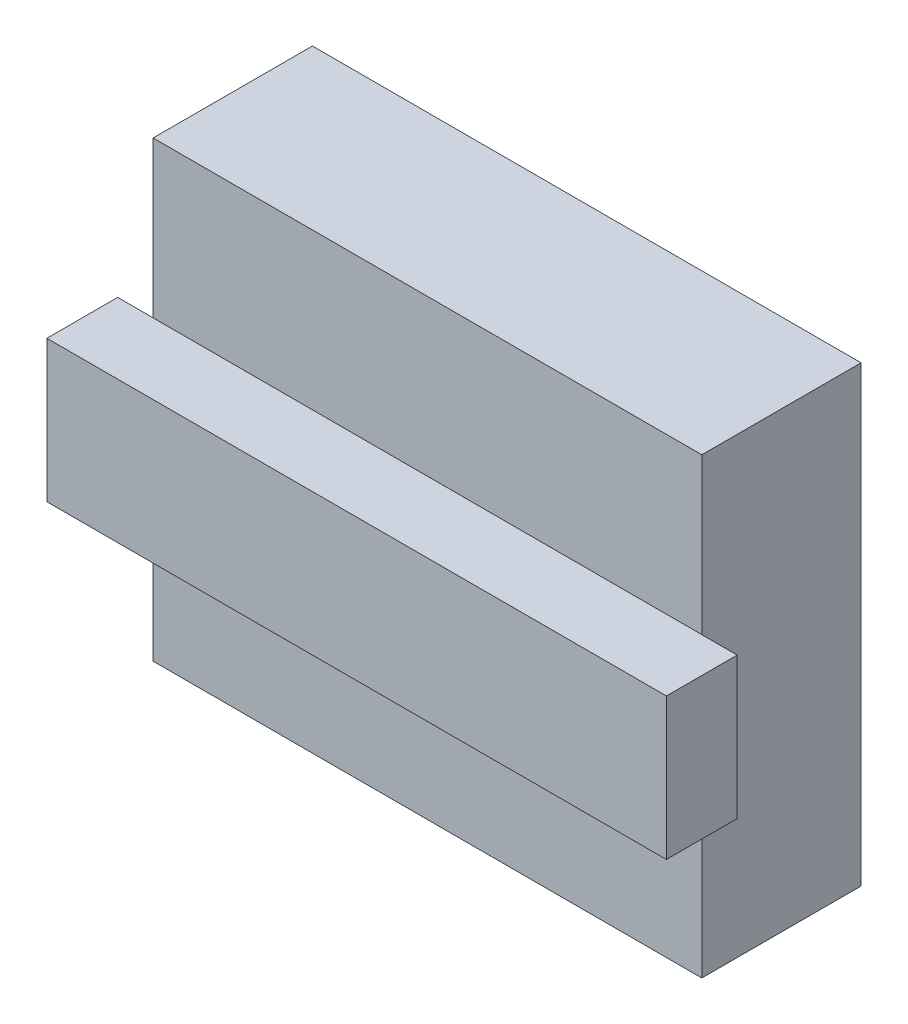
SolidWorks part; units mm, degrees
ref_plane "Front Plane" through (0, 0, 0) normal (0, 0, 1) x (1, 0, 0)
ref_plane "Top Plane" through (0, 0, 0) normal (0, 1, 0) x (1, 0, 0)
ref_plane "Right Plane" through (0, 0, 0) normal (1, 0, 0) x (0, 0, -1)
sketch "Sketch1" plane through (0, 0, 0) normal (0, 0, 1) x (1, 0, 0)
  line L5 (-7.75, -6.4) -> (7.75, -6.4)
  line L6 (-7.75, -6.4) -> (-7.75, 6.4)
  line L7 (-7.75, 6.4) -> (7.75, 6.4)
  line L8 (7.75, -6.4) -> (7.75, 6.4)
  line L9 (-7.75, -6.4) -> (7.75, 6.4) construction
  line L10 (-7.75, 6.4) -> (7.75, -6.4) construction
  point P0 (0, 0)
  dimension "D1" = 15.5
  dimension "D2" = 12.8
extrude "Boss-Extrude1" add sketch "Sketch1" along normal blind 4.5
sketch "Sketch2" plane through (0, 0, 0) normal (0, 0, -1) x (1, 0, 0)
  circle A0 centre (0, 0) radius 1
extrude "Boss-Extrude2" add sketch "Sketch2" along normal blind 4
sketch "Sketch3" plane through (0, 0, 4.5) normal (0, 0, 1) x (1, 0, 0)
  line L0 (-7.75, 6.4) -> (-7.75, -6.4) construction
  line L2 (-7.75, 2) -> (-8.75, 2)
  line L3 (-8.75, 2) -> (-8.75, -2)
  line L4 (-8.75, -2) -> (-7.75, -2)
  line L5 (0, 6.4) -> (0, -6.4) construction
  line L6 (7.75, 6.4) -> (-7.75, 6.4) construction
  line L7 (-7.75, -6.4) -> (7.75, -6.4) construction
  line L8 (8.75, -2) -> (7.75, -2)
  line L9 (8.75, 2) -> (8.75, -2)
  line L10 (7.75, 2) -> (8.75, 2)
  line L11 (-7.75, 2) -> (7.75, 2)
  line L12 (-7.75, -2) -> (7.75, -2)
  dimension "D1" = 1
  dimension "D2" = 4
extrude "Boss-Extrude3" add sketch "Sketch3" along normal blind 2
